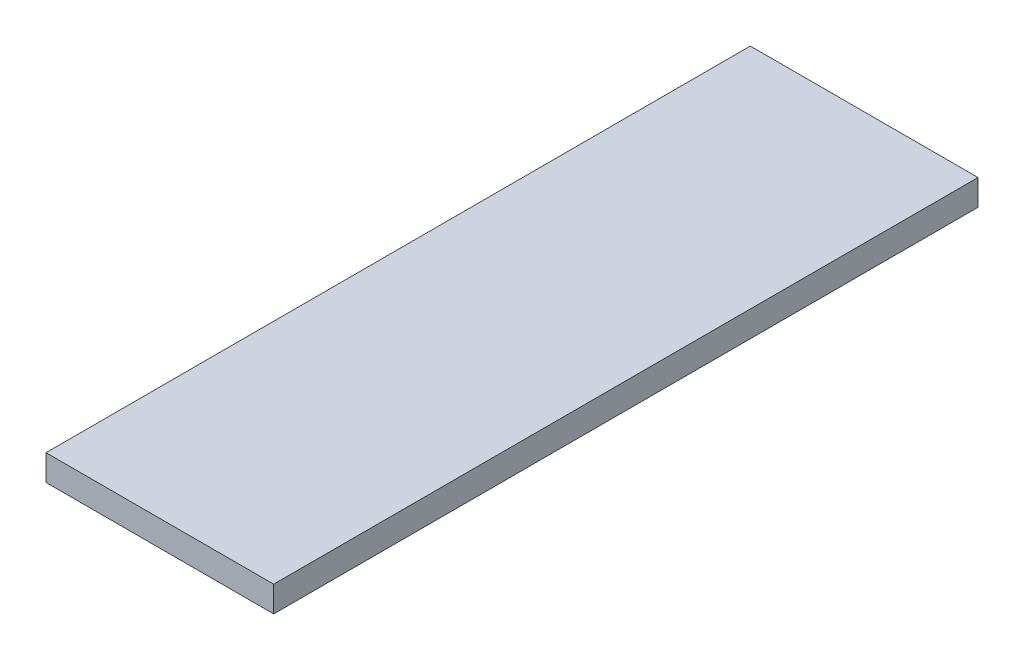
SolidWorks part; units mm, degrees
ref_plane "Front Plane" through (0, 0, 0) normal (0, 0, 1) x (1, 0, 0)
ref_plane "Top Plane" through (0, 0, 0) normal (0, 1, 0) x (1, 0, 0)
ref_plane "Right Plane" through (0, 0, 0) normal (1, 0, 0) x (0, 0, -1)
sketch "Sketch1" plane through (0, 0, 0) normal (0, 0, 1) x (1, 0, 0)
  line L0 (230, -400.5) -> (80, -400.5) construction
  line L1 (80, -383.5) -> (80, -400.5) construction
  line L2 (230, -383.5) -> (80, -383.5) construction
  line L3 (230, -383.5) -> (230, -400.5) construction
  line L4 (230, -400.5) -> (80, -400.5)
  line L5 (80, -383.5) -> (80, -400.5)
  line L6 (230, -383.5) -> (80, -383.5)
  line L7 (230, -383.5) -> (230, -400.5)
extrude "Boss-Extrude1" add sketch "Sketch1" along normal up to surface (464 mm away)
